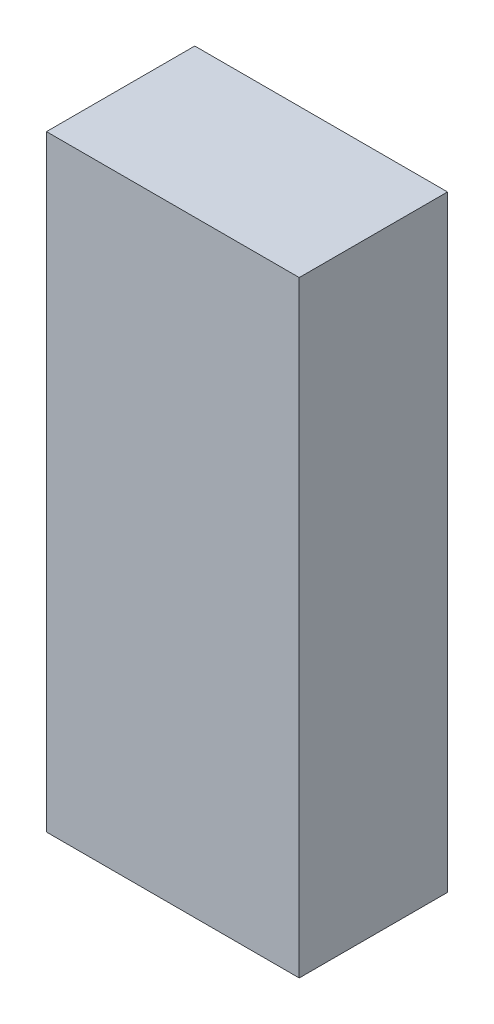
SolidWorks part; units mm, degrees
ref_plane "Front Plane" through (0, 0, 0) normal (0, 0, 1) x (1, 0, 0)
ref_plane "Top Plane" through (0, 0, 0) normal (0, 1, 0) x (1, 0, 0)
ref_plane "Right Plane" through (0, 0, 0) normal (1, 0, 0) x (0, 0, -1)
sketch "Sketch1" plane through (0, 0, 0) normal (0, 0, 1) x (1, 0, 0)
  line L1 (0, 0) -> (9.525, 0)
  line L2 (0, 0) -> (0, 22.86)
  line L3 (0, 22.86) -> (9.525, 22.86)
  line L4 (9.525, 0) -> (9.525, 22.86)
  dimension "D1" = 9.525
  dimension "D2" = 22.86
extrude "Boss-Extrude1" add sketch "Sketch1" along normal blind 5.588
